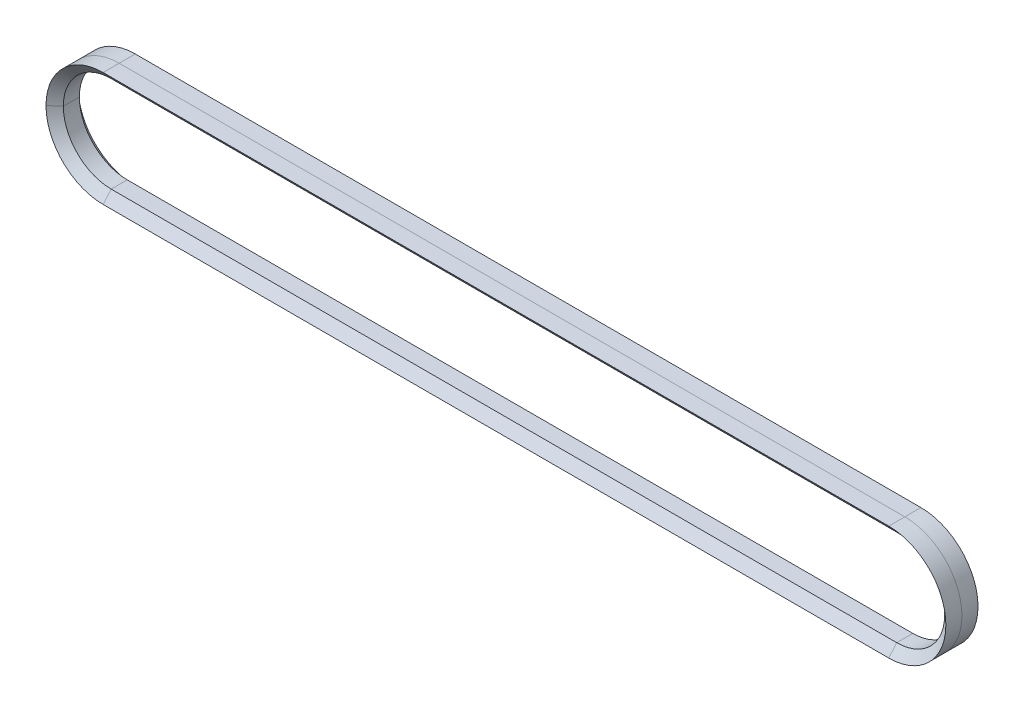
SolidWorks part; units mm, degrees
ref_plane "前视基准面" through (0, 0, 0) normal (0, 0, 1) x (1, 0, 0)
ref_plane "上视基准面" through (0, 0, 0) normal (0, 1, 0) x (1, 0, 0)
ref_plane "右视基准面" through (0, 0, 0) normal (1, 0, 0) x (0, 0, -1)
sketch "草图1" plane through (0, 0, 0) normal (0, 0, 1) x (1, 0, 0)
  line L0 (-90, 16) -> (130, 16)
  line L1 (130, -16) -> (-90, -16)
  arc A0 (-90, 16) -> (-90, -16) centre (-90, 0) ccw
  arc A1 (130, 16) -> (130, -16) centre (130, 0) cw
sketch "草图2" plane through (0, 0, 0) normal (0, 1, 0) x (1, 0, 0)
  line L0 (-106, 0) -> (-106, 4.5)
  line L1 (-106, 0) -> (-90, 0) construction
  line L2 (-106, 0) -> (-106, -4.5)
  line L3 (-103.4, 2.25) -> (-103.4, -2.25)
  line L4 (-106, 4.5) -> (-103.4, 2.25)
  line L5 (-103.4, -2.25) -> (-106, -4.5)
  dimension "D1" = 2.6
  dimension "D2" = 4.5
sweep "扫描1" add profiles "草图2" path "草图1"
